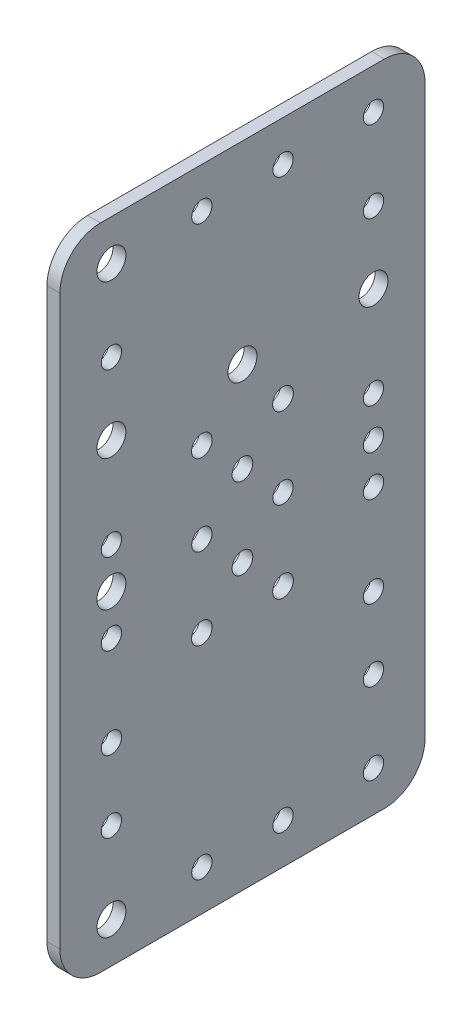
SolidWorks part; units mm, degrees
ref_plane "Front Plane" through (0, 0, 0) normal (0, 0, 1) x (1, 0, 0)
ref_plane "Top Plane" through (0, 0, 0) normal (0, 1, 0) x (1, 0, 0)
ref_plane "Right Plane" through (0, 0, 0) normal (1, 0, 0) x (0, 0, -1)
ref_plane "Plane1" through (0, 0, 0) normal (-1, 0, 0) x (0, -1, 0)
sketch "Sketch1" plane through (0, 0, 0) normal (-1, 0, 0) x (0, -1, 0)
  line L0 (-80, 35) -> (-80, -35)
  line L1 (-70, -45) -> (70, -45)
  line L2 (80, -35) -> (80, 35)
  line L3 (70, 45) -> (-70, 45)
  circle A0 centre (50, 32.3) radius 2.5
  circle A1 centre (50, -32.3) radius 2.5
  circle A2 centre (-50, 32.3) radius 2.5
  circle A3 centre (-50, -32.3) radius 2.5
  circle A4 centre (10, 0) radius 2.55
  circle A5 centre (-10, 0) radius 2.55
  circle A6 centre (-20, 10) radius 2.55
  circle A7 centre (-20, -10) radius 2.55
  circle A8 centre (20, 10) radius 2.55
  circle A9 centre (20, -10) radius 2.55
  circle A10 centre (-70, 10) radius 2.5
  circle A11 centre (70, 10) radius 2.5
  circle A12 centre (-70, -10) radius 2.5
  circle A13 centre (70, -10) radius 2.5
  circle A14 centre (10, -32.3) radius 2.5
  circle A15 centre (10, 32.3) radius 2.5
  circle A16 centre (-10, 32.3) radius 2.5
  circle A17 centre (-32.3, -32.3) radius 3.5685
  circle A18 centre (-32.3, 0) radius 3.5685
  circle A19 centre (-32.3, 32.3) radius 3.5685
  circle A20 centre (32.3, 32.3) radius 2.5
  circle A21 centre (32.3, -32.3) radius 2.5
  circle A22 centre (-10, -32.3) radius 2.5
  circle A23 centre (0, 10) radius 2.5
  circle A24 centre (0, -10) radius 2.5
  circle A25 centre (70, 32.3) radius 3.5685
  circle A26 centre (0, 32.3) radius 3.5685
  circle A27 centre (-70, 32.3) radius 3.5685
  circle A28 centre (-70, -32.3) radius 2.5
  circle A29 centre (70, -32.3) radius 2.5
  circle A30 centre (0, -32.3) radius 2.5
  arc A31 (-70, 45) -> (-80, 35) centre (-70, 35) ccw
  arc A32 (-80, -35) -> (-70, -45) centre (-70, -35) ccw
  arc A33 (70, -45) -> (80, -35) centre (70, -35) ccw
  arc A34 (80, 35) -> (70, 45) centre (70, 35) ccw
extrude "Boss-Extrude1" add sketch "Sketch1" against normal blind 3.175
